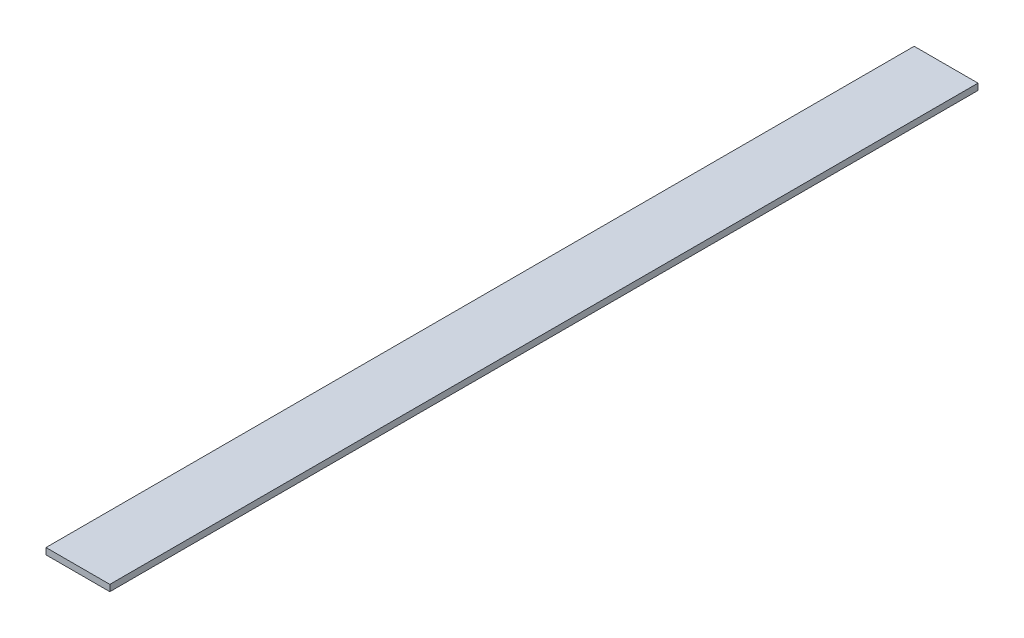
SolidWorks part; units mm, degrees
ref_plane "Płaszczyzna przednia" through (0, 0, 0) normal (0, 0, 1) x (1, 0, 0)
ref_plane "Płaszczyzna górna" through (0, 0, 0) normal (0, 1, 0) x (1, 0, 0)
ref_plane "Płaszczyzna prawa" through (0, 0, 0) normal (1, 0, 0) x (0, 0, -1)
sketch "Szkic1" plane through (0, 0, 0) normal (0, 0, 1) x (1, 0, 0)
  line L1 (0, 0) -> (50, 0)
  line L2 (0, 0) -> (0, 5)
  line L3 (0, 5) -> (50, 5)
  line L4 (50, 0) -> (50, 5)
  dimension "D1" = 50
  dimension "D2" = 5
extrude "Dodanie-wyciągnięcie1" add sketch "Szkic1" along normal blind 680
